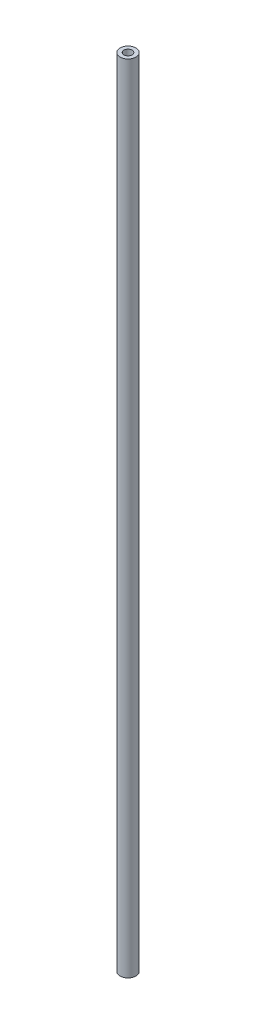
SolidWorks part; units mm, degrees
ref_plane "Front Plane" through (0, 0, 0) normal (0, 0, 1) x (1, 0, 0)
ref_plane "Top Plane" through (0, 0, 0) normal (0, 1, 0) x (1, 0, 0)
ref_plane "Right Plane" through (0, 0, 0) normal (1, 0, 0) x (0, 0, -1)
sketch "Sketch1" plane through (0, 0, 0) normal (0, 1, 0) x (1, 0, 0)
  circle A0 centre (0, 0) radius 5
  dimension "D1" = 10
extrude "Boss-Extrude1" add sketch "Sketch1" along normal blind 500
sketch "Sketch2" plane through (0, 0, 0) normal (0, -1, 0) x (1, 0, 0)
  circle A0 centre (0, 0) radius 2.6
  dimension "D1" = 5.2
extrude "Cut-Extrude1" cut sketch "Sketch2" against normal blind 10
sketch "Sketch3" plane through (0, 500, 0) normal (0, 1, 0) x (1, 0, 0)
  circle A0 centre (0, 0) radius 2.6
  dimension "D1" = 5.2
extrude "Cut-Extrude2" cut sketch "Sketch3" against normal blind 10
